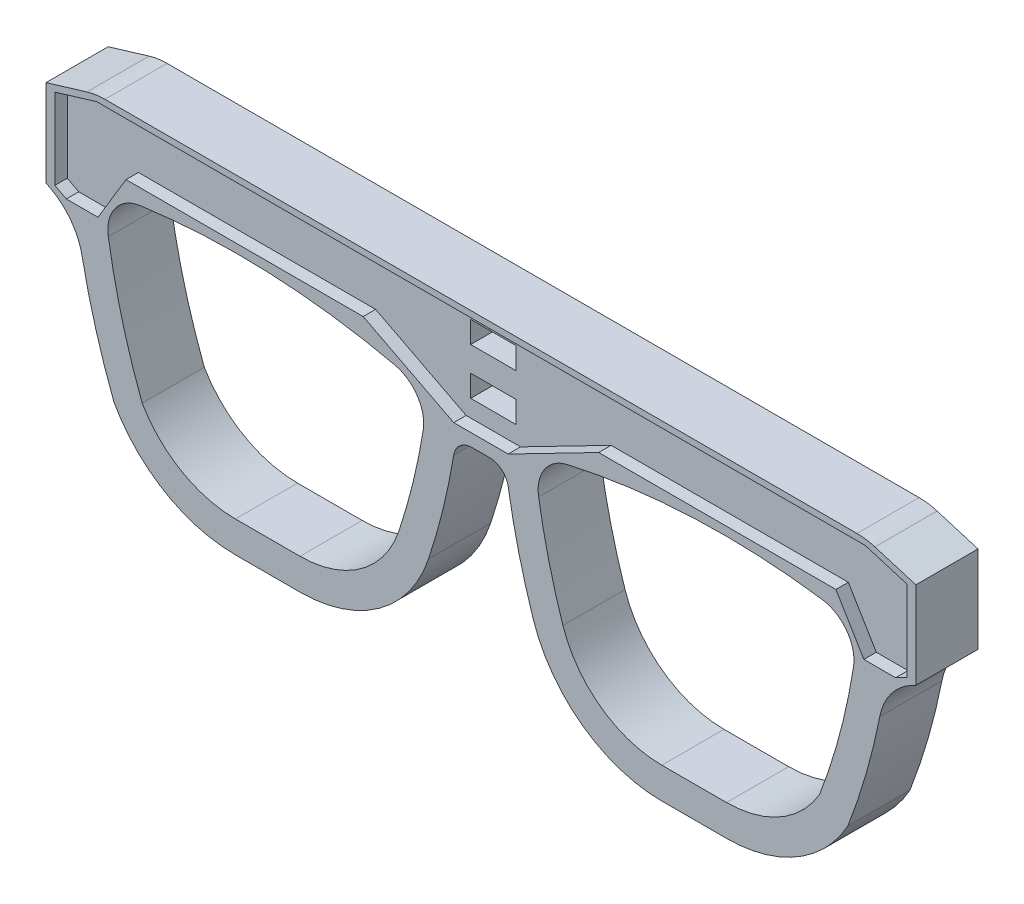
SolidWorks part; units mm, degrees
ref_plane "Front Plane" through (0, 0, 0) normal (0, 0, 1) x (1, 0, 0)
ref_plane "Top Plane" through (0, 0, 0) normal (0, 1, 0) x (1, 0, 0)
ref_plane "Right Plane" through (0, 0, 0) normal (1, 0, 0) x (0, 0, -1)
sketch "Sketch1" plane through (0, 0, 0) normal (0, 0, 1) x (1, 0, 0)
  line L4 (-70, 16.5826) -> (-70, 2.5826)
  line L5 (-70, 2.5826) -> (-65, -0.0353)
  line L6 (-39.5244, -34) -> (-29.1194, -34)
  line L7 (-4, 0) -> (0, 0)
  line L8 (0, 45.3197) -> (0, -37.9766) construction
  line L11 (-62, 19) -> (0, 19)
  line L12 (0, 19) -> (0, 0)
  line L13 (-70, 16.5826) -> (-62, 19)
  arc A2 (-8.4439, -19.0581) -> (-4, 0) centre (-111.6609, 15.057) ccw
  arc A3 (-65, -0.0353) -> (-59.0574, -22.499) centre (40.965, 15.9791) ccw
  arc A4 (-59.0574, -22.499) -> (-39.5244, -34) centre (-39.5244, -11.6623) ccw
  arc A5 (-29.1194, -34) -> (-8.4439, -19.0581) centre (-29.1194, -12.2244) ccw
  point P4 (-65, 21)
  point P7 (0, 0)
  point P20 (0, -37.9766)
  point P21 (-65, 19)
  point P22 (-70, 14.7143)
  point P23 (0, 0)
  point P24 (-70, 16.5826)
  dimension "D8" = 5
  dimension "D1" = 4
  dimension "D2" = 53
  dimension "D3" = 34
  dimension "D4" = 70
  dimension "D5" = 8
  dimension "D7" = 14
extrude "Boss-Extrude1" add sketch "Sketch1" along normal blind 10 contours L4 L5 A3 A4 L6 A5 A2 L7 L12 L11 L13
sketch "Sketch2" plane through (0, 0, 10) normal (0, 0, 1) x (1, 0, 0)
  line L7 (-39.5244, -29) -> (-29.1194, -29)
  line L8 (-39.5244, -29) -> (-29.1194, -29)
  arc A15 (-60.0561, 0.7118) -> (-59.2887, 6.3037) centre (-50.178, 2.2047) cw
  arc A16 (-59.2887, 6.3037) -> (-8.9375, 4.059) centre (-39.064, -105.8745) cw
  arc A17 (-8.9375, 4.059) -> (-8.9518, 0.6925) centre (-21.3647, 2.4286) cw
  arc A19 (-13.1913, -17.489) -> (-8.9518, 0.6925) centre (-111.6609, 15.057) ccw
  arc A20 (-29.1194, -29) -> (-13.1913, -17.489) centre (-29.1194, -12.2244) ccw
  arc A21 (-54.5219, -20.3612) -> (-39.5244, -29) centre (-39.5244, -11.6623) ccw
  arc A22 (-60.0561, 0.7118) -> (-54.5219, -20.3612) centre (40.965, 15.9791) ccw
  arc A23 (-13.1913, -17.489) -> (-8.9518, 0.6925) centre (-111.6609, 15.057) ccw
  arc A24 (-29.1194, -29) -> (-13.1913, -17.489) centre (-29.1194, -12.2244) ccw
  arc A25 (-54.5219, -20.3612) -> (-39.5244, -29) centre (-39.5244, -11.6623) ccw
  arc A26 (-60.0561, 0.7118) -> (-54.5219, -20.3612) centre (40.965, 15.9791) ccw
  point P5 (-58.6445, 7.3414)
  point P6 (-8.954, 4.0698)
  point P7 (-59.2984, 6.3081)
  dimension "D1" = 5
extrude "Cut-Extrude1" cut sketch "Sketch2" against normal through all
fillet "Fillet1" radius 6 2 edges at (-8.9375, 4.059, 5) (-59.2887, 6.3037, 5)
sketch "Sketch3" plane through (0, 0, 10) normal (0, 0, 1) x (1, 0, 0)
  line L0 (-68.579, 15.9673) -> (-61.8522, 18)
  line L1 (-70, 16.5826) -> (-62, 19) construction
  line L2 (-4.3821, 2) -> (4.3821, 2)
  line L4 (0, 2) -> (0, 18)
  line L5 (61.8522, 18) -> (-61.8522, 18)
  line L7 (-68.579, 15.9673) -> (-68.579, 2.9673)
  line L8 (-66.7315, 2) -> (-61.6323, 2)
  line L9 (-61.6323, 2) -> (-57.1269, 9.5)
  line L10 (-57.1269, 9.5) -> (-18.9511, 9.5)
  line L11 (-18.9511, 9.5) -> (-4.3821, 2)
  line L12 (-62, 19) -> (0, 19) construction
  line L13 (-4, 0) -> (0, 0) construction
  line L14 (-68.579, 2.9673) -> (-66.7315, 2)
  line L15 (-70, 2.5826) -> (-65, -0.0353) construction
  line L16 (68.579, 15.9673) -> (61.8522, 18)
  line L17 (18.9511, 9.5) -> (4.3821, 2)
  line L18 (57.1269, 9.5) -> (18.9511, 9.5)
  line L19 (61.6323, 2) -> (57.1269, 9.5)
  line L20 (66.7315, 2) -> (61.6323, 2)
  line L21 (68.579, 2.9673) -> (66.7315, 2)
  line L22 (68.579, 15.9673) -> (68.579, 2.9673)
  arc A1 (-13.8821, 5.2959) -> (-54.8725, 7.0107) centre (-39.064, -105.8745) ccw construction
  point P40 (-39.064, 8.1123)
  dimension "D2" = 2
  dimension "D1" = 1
  dimension "D3" = 8.5
  dimension "D4" = 1
  dimension "D5" = 1
fillet "Fillet4" radius 3 1 edges at (-4, 0, 5)
fillet "Fillet5" radius 10 2 edges at (-65, -0.0353, 5) (-62, 19, 5)
mirror "Mirror2" about plane through (0, 19, 10) normal (1, 0, 0) of "Fillet5", "Fillet4", "Boss-Extrude1", "Cut-Extrude1", "Fillet1"
extrude "Cut-Extrude2" cut sketch "Sketch3" against normal blind 2 contours L5 L0 L7 L14 L8 L9 L10 L11 L2 L17 L18 L19 L20 L21 L22 L16
sketch "Sketch4" plane through (0, 0, 8) normal (0, 0, 1) x (1, 0, 0)
  line L0 (-4.3821, 2) -> (4.3821, 2) construction
  line L1 (3.65, 15.75) -> (-3.65, 15.75)
  line L2 (3.65, 15.75) -> (3.65, 12.25)
  line L3 (3.65, 12.25) -> (-3.65, 12.25)
  line L4 (-3.65, 15.75) -> (-3.65, 12.25)
  line L5 (3.65, 15.75) -> (-3.65, 12.25) construction
  line L6 (3.65, 12.25) -> (-3.65, 15.75) construction
  line L7 (3.65, 8.25) -> (-3.65, 8.25)
  line L8 (3.65, 8.25) -> (3.65, 4.75)
  line L9 (3.65, 4.75) -> (-3.65, 4.75)
  line L10 (-3.65, 8.25) -> (-3.65, 4.75)
  line L11 (3.65, 8.25) -> (-3.65, 4.75) construction
  line L12 (3.65, 4.75) -> (-3.65, 8.25) construction
  point P0 (0, 14)
  point P5 (0, 6.5)
  point P10 (0, 0)
  dimension "D1" = 3.5
  dimension "D2" = 7.3
  dimension "D3" = 4.5
  dimension "D4" = 12
extrude "Cut-Extrude3" cut sketch "Sketch4" against normal through all
sketch "Sketch5" plane through (0, 19, 0) normal (0, 1, 0) x (1, 0, 0)
  line L0 (-60.5221, 0) -> (60.5221, 0) construction
  line L1 (7, -10) -> (-7, -10) construction
  line L2 (7, -10) -> (7, 0) construction
  line L3 (7, 0) -> (-7, 0) construction
  line L4 (-7, -10) -> (-7, 0) construction
  line L5 (7, -10) -> (-7, 0) construction
  line L6 (7, 0) -> (-7, -10) construction
  line L7 (-60.5221, -10) -> (60.5221, -10) construction
  point P0 (0, -5)
  point P10 (0, 0)
  dimension "D1" = 14
